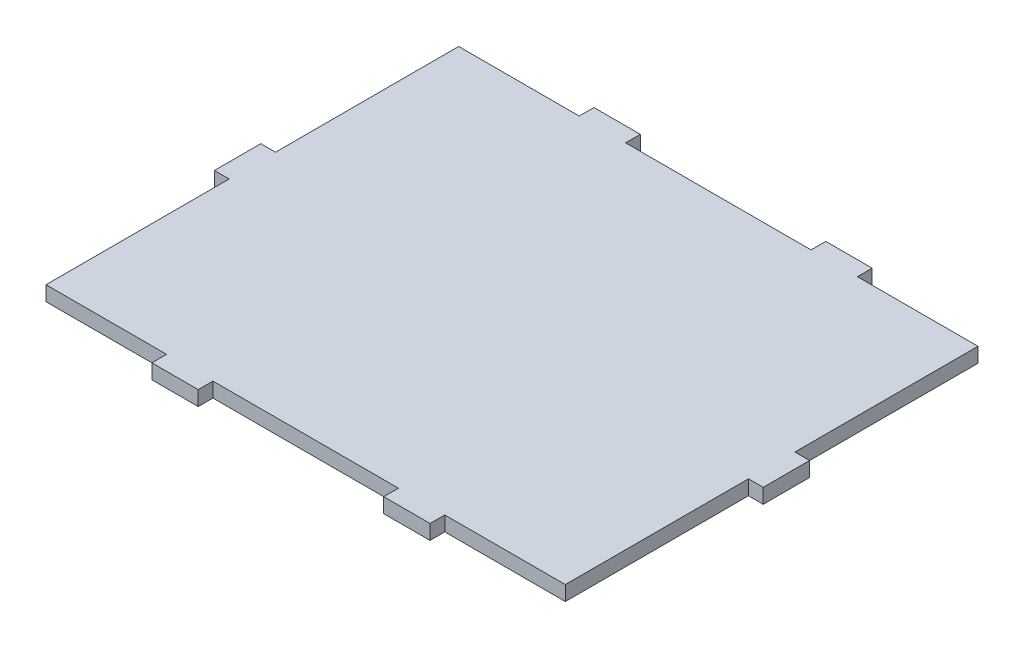
SolidWorks part; units mm, degrees
ref_plane "Front Plane" through (0, 0, 0) normal (0, 0, 1) x (1, 0, 0)
ref_plane "Top Plane" through (0, 0, 0) normal (0, 1, 0) x (1, 0, 0)
ref_plane "Right Plane" through (0, 0, 0) normal (1, 0, 0) x (0, 0, -1)
sketch "Sketch1" plane through (0, 0, 0) normal (0, 1, 0) x (1, 0, 0)
  line L1 (-56, -47.675) -> (56, -47.675)
  line L2 (-56, -47.675) -> (-56, 47.675)
  line L3 (-56, 47.675) -> (56, 47.675)
  line L4 (56, -47.675) -> (56, 47.675)
  line L5 (-56, -47.675) -> (56, 47.675) construction
  line L6 (-56, 47.675) -> (56, -47.675) construction
  point P0 (0, 0)
  dimension "D1" = 112
  dimension "D2" = 95.35
extrude "Boss-Extrude1" add sketch "Sketch1" along normal blind 3.175
sketch "Sketch2" plane through (0, 3.175, 0) normal (0, 1, 0) x (1, 0, 0)
  line L0 (56, 47.675) -> (-56, 47.675) construction
  line L1 (-20, 47.675) -> (20, 47.675)
  line L2 (-20, 47.675) -> (-20, 44.5)
  line L3 (-20, 44.5) -> (20, 44.5)
  line L4 (20, 47.675) -> (20, 44.5)
  line L6 (56, -47.675) -> (56, 47.675) construction
  line L7 (30, 47.675) -> (56, 47.675)
  line L8 (30, 47.675) -> (30, 44.5)
  line L9 (30, 44.5) -> (56, 44.5)
  line L10 (56, 47.675) -> (56, 44.5)
  line L11 (-56, -47.675) -> (56, -47.675) construction
  line L12 (-56, 47.675) -> (-30, 47.675)
  line L13 (-56, 47.675) -> (-56, 44.5)
  line L14 (-56, 44.5) -> (-30, 44.5)
  line L15 (-30, 47.675) -> (-30, 44.5)
  line L16 (-20, -47.675) -> (20, -47.675)
  line L17 (-20, -47.675) -> (-20, -44.5)
  line L18 (-20, -44.5) -> (20, -44.5)
  line L19 (20, -47.675) -> (20, -44.5)
  line L21 (-30, -44.5) -> (-56, -44.5)
  line L22 (-30, -44.5) -> (-30, -47.675)
  line L23 (-30, -47.675) -> (-56, -47.675)
  line L24 (-56, -44.5) -> (-56, -47.675)
  line L25 (30, -44.5) -> (56, -44.5)
  line L26 (30, -44.5) -> (30, -47.675)
  line L27 (30, -47.675) -> (56, -47.675)
  line L28 (56, -44.5) -> (56, -47.675)
  dimension "D1" = 40
  dimension "D2" = 3.175
  dimension "D3" = 20
  dimension "D4" = 10
  dimension "D5" = 10
  dimension "D6" = 40
  dimension "D7" = 20
  dimension "D8" = 3.175
extrude "Cut-Extrude1" cut sketch "Sketch2" against normal through all
sketch "Sketch4" plane through (-56, 0, 0) normal (-1, 0, 0) x (0, 0, 1)
  line L0 (-44.5, 3.175) -> (44.5, 3.175) construction
  line L1 (-5, 3.175) -> (5, 3.175)
  line L2 (-5, 3.175) -> (-5, 0)
  line L3 (-5, 0) -> (5, 0)
  line L4 (5, 3.175) -> (5, 0)
  line L5 (-44.5, 0) -> (44.5, 0) construction
  dimension "D1" = 10
  dimension "D2" = 5
extrude "Boss-Extrude2" add sketch "Sketch4" along normal blind 3.175
sketch "Sketch5" plane through (56, 0, 0) normal (1, 0, 0) x (0, 0, -1)
  line L0 (-44.5, 3.175) -> (44.5, 3.175) construction
  line L1 (-5, 3.175) -> (5, 3.175)
  line L2 (-5, 3.175) -> (-5, 0)
  line L3 (-5, 0) -> (5, 0)
  line L4 (5, 3.175) -> (5, 0)
  dimension "D1" = 10
extrude "Boss-Extrude3" add sketch "Sketch5" along normal blind 3.175
